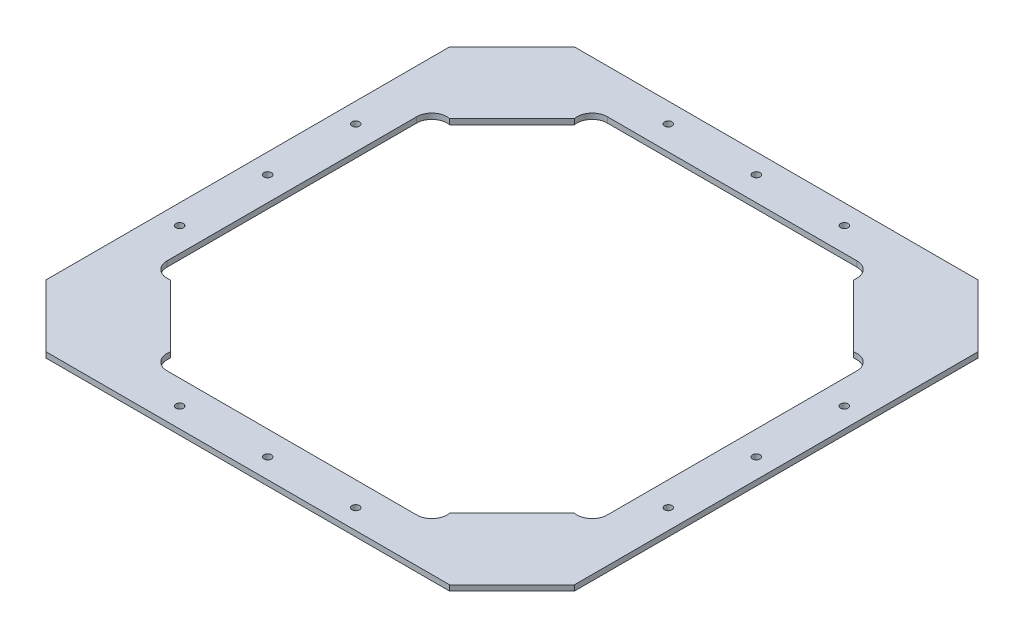
SolidWorks part; units mm, degrees
ref_plane "Front Plane" through (0, 0, 0) normal (0, 0, 1) x (1, 0, 0)
ref_plane "Top Plane" through (0, 0, 0) normal (0, 1, 0) x (1, 0, 0)
ref_plane "Right Plane" through (0, 0, 0) normal (1, 0, 0) x (0, 0, -1)
sketch "Sketch2" plane through (0, 0, 0) normal (0, 1, 0) x (1, 0, 0)
  line L0 (-152.4, 116.479) -> (-116.479, 152.4)
  line L1 (-116.479, 152.4) -> (116.479, 152.4)
  line L2 (-152.4, 116.479) -> (-152.4, -116.479)
  line L3 (-116.479, 80.558) -> (-80.558, 116.479)
  line L4 (-134.4395, 134.4395) -> (-98.5185, 98.5185) construction
  line L5 (-59.329, 127) -> (59.329, 127)
  line L6 (-127, 59.329) -> (-127, -59.329)
  line L7 (-59.329, 127) -> (-72.029, 127)
  line L8 (-127, 59.329) -> (-127, 72.029)
  line L9 (0, -208.1331) -> (0, 208.1331) construction
  line L10 (190.1851, 0) -> (-190.1851, 0) construction
  line L11 (134.4395, 134.4395) -> (98.5185, 98.5185) construction
  line L12 (127, 59.329) -> (127, 72.029)
  line L13 (59.329, 127) -> (72.029, 127)
  line L14 (127, 59.329) -> (127, -59.329)
  line L15 (116.479, 80.558) -> (80.558, 116.479)
  line L16 (152.4, 116.479) -> (152.4, -116.479)
  line L17 (152.4, 116.479) -> (116.479, 152.4)
  line L18 (134.4395, -134.4395) -> (98.5185, -98.5185) construction
  line L19 (-134.4395, -134.4395) -> (-98.5185, -98.5185) construction
  line L20 (152.4, -116.479) -> (116.479, -152.4)
  line L21 (116.479, -80.558) -> (80.558, -116.479)
  line L22 (59.329, -127) -> (72.029, -127)
  line L23 (127, -59.329) -> (127, -72.029)
  line L24 (-127, -59.329) -> (-127, -72.029)
  line L25 (-59.329, -127) -> (-72.029, -127)
  line L26 (-59.329, -127) -> (59.329, -127)
  line L27 (-116.479, -80.558) -> (-80.558, -116.479)
  line L28 (-116.479, -152.4) -> (116.479, -152.4)
  line L29 (-152.4, -116.479) -> (-116.479, -152.4)
  arc A0 (-72.029, 127) -> (-80.558, 116.479) centre (-72.029, 118.2824) ccw
  arc A1 (-127, 72.029) -> (-116.479, 80.558) centre (-118.2824, 72.029) cw
  arc A2 (127, 72.029) -> (116.479, 80.558) centre (118.2824, 72.029) ccw
  arc A3 (72.029, 127) -> (80.558, 116.479) centre (72.029, 118.2824) cw
  arc A4 (72.029, -127) -> (80.558, -116.479) centre (72.029, -118.2824) ccw
  arc A5 (127, -72.029) -> (116.479, -80.558) centre (118.2824, -72.029) cw
  arc A6 (-127, -72.029) -> (-116.479, -80.558) centre (-118.2824, -72.029) ccw
  arc A7 (-72.029, -127) -> (-80.558, -116.479) centre (-72.029, -118.2824) cw
  point P1 (0, 127)
  point P25 (0, 127)
  point P26 (0, 152.4)
  point P35 (0, 127)
  point P38 (0, 152.4)
  point P41 (0, 0)
  point P56 (-127, 0)
  point P57 (-152.4, 0)
  point P58 (0, -152.4)
  point P59 (0, -127)
  point P61 (152.4, 0)
  point P62 (127, 0)
  point P65 (-127, 0)
  point P66 (-152.4, 0)
  dimension "D10" = 50.8
  dimension "D13" = 12.7
  dimension "D14" = 12.7
  dimension "D1" = 50.8
  dimension "D2" = 25.4
  dimension "D3" = 25.4
  dimension "D4" = 50.8
  dimension "D5" = 152.4
  dimension "D6" = 152.4
  dimension "D7" = 45
  dimension "D8" = 135
  dimension "D9" = 90
  dimension "D11" = 57.15
  dimension "D12" = 57.15
extrude "Boss-Extrude1" add sketch "Sketch2" along normal blind 3.175
sketch "Sketch4" plane through (0, 3.175, 0) normal (0, 1, 0) x (1, 0, 0)
  line L0 (0, 201.0925) -> (0, -226.4518) construction
  line L1 (-181.7718, 0) -> (192.408, 0) construction
  line L2 (116.479, 152.4) -> (-116.479, 152.4) construction
  line L3 (-152.4, 116.479) -> (-152.4, -116.479) construction
  circle A0 centre (0, 140.97) radius 2.159
  circle A1 centre (-50.8, 140.97) radius 2.159
  circle A2 centre (-140.97, 50.8) radius 2.159
  circle A3 centre (-140.97, 0) radius 2.159
  circle A4 centre (140.97, 0) radius 2.159
  circle A5 centre (140.97, 50.8) radius 2.159
  circle A6 centre (50.8, 140.97) radius 2.159
  circle A7 centre (50.8, -140.97) radius 2.159
  circle A8 centre (140.97, -50.8) radius 2.159
  circle A9 centre (-50.8, -140.97) radius 2.159
  circle A10 centre (0, -140.97) radius 2.159
  circle A11 centre (-140.97, -50.8) radius 2.159
  dimension "D1" = 4.318
  dimension "D2" = 4.318
  dimension "D3" = 4.318
  dimension "D4" = 4.318
  dimension "D5" = 11.43
  dimension "D6" = 11.43
  dimension "D7" = 50.8
  dimension "D8" = 11.43
  dimension "D9" = 11.43
  dimension "D10" = 50.8
extrude "Cut-Extrude2" cut sketch "Sketch4" against normal through all
